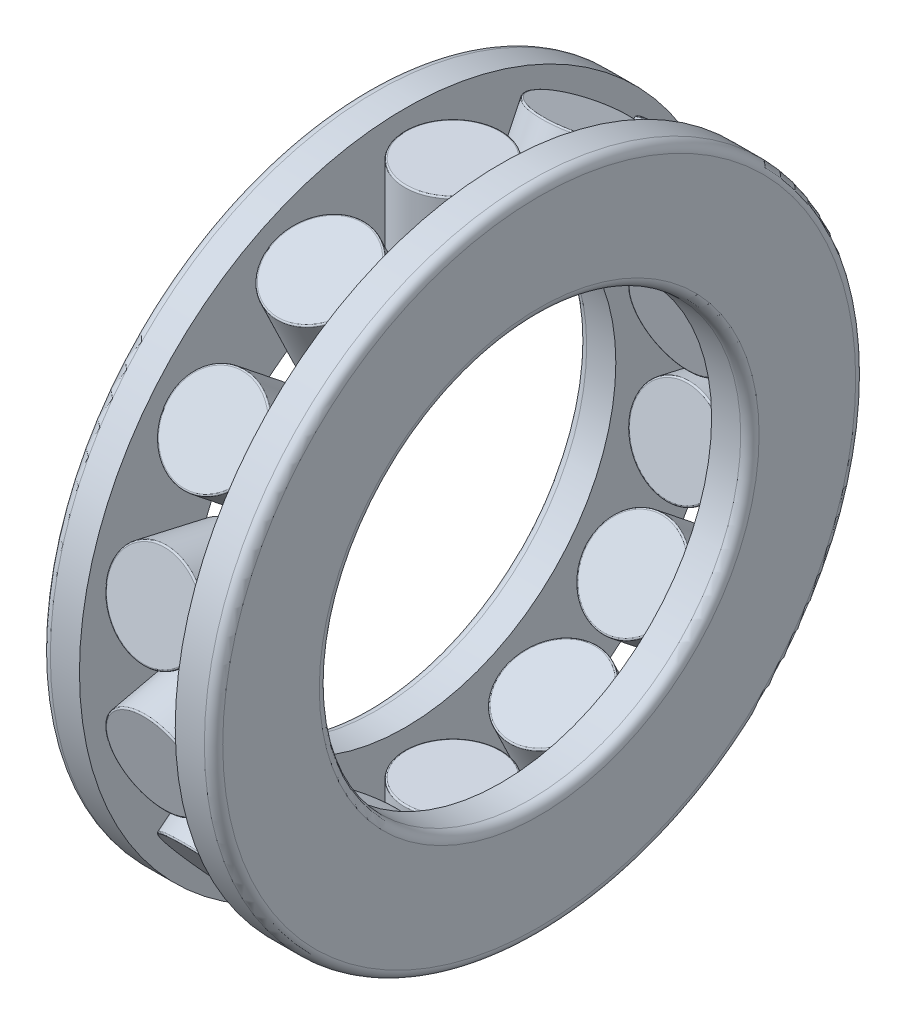
SolidWorks part; units mm, degrees
ref_plane "Plane1" through (0, 0, 0) normal (0, 0, 1) x (1, 0, 0)
ref_plane "Plane2" through (0, 0, 0) normal (0, 1, 0) x (1, 0, 0)
ref_plane "Plane3" through (0, 0, 0) normal (1, 0, 0) x (0, 0, -1)
sketch "Clipboard" plane through (0, 0, 0) normal (0, 0, 1) x (1, 0, 0)
  line L0 (-10, 0) -> (10, 0) construction
  line L1 (0, 0) -> (21.6965, -5.4095)
  line L2 (0, 0) -> (27.3662, 35.0271)
  line L3 (0, 0) -> (13.7666, -17.6205)
  line L4 (0, 0) -> (-22.3471, -0.7804)
  dimension "BallCLRad" = 44.45
  dimension "Count" = 52
  dimension "Show_count" = 52
  dimension "Max_count" = 14
  dimension "Min_count" = 2
sketch "InnRacSke" plane through (0, 0, 0) normal (0, 0, 1) x (1, 0, 0)
  line L1 (-7.9375, 34.925) -> (-12.7635, 34.925)
  line L2 (-14.2875, 36.449) -> (-14.2875, 52.451)
  line L3 (-12.7635, 53.975) -> (-7.9375, 53.975)
  line L4 (-7.9375, 53.975) -> (-7.9375, 34.925)
  line L5 (-34.925, 0) -> (34.925, 0) construction
  line L6 (0, 0) -> (0, 25.4) construction
  arc A0 (-12.7635, 34.925) -> (-14.2875, 36.449) centre (-12.7635, 36.449) cw
  arc A1 (-14.2875, 52.451) -> (-12.7635, 53.975) centre (-12.7635, 52.451) cw
  dimension "ID" = 69.85
  dimension "OD" = 107.95
  dimension "Width" = 28.575
  dimension "gap" = 15.875
revolve "Race" add sketch "InnRacSke" angle 360 about L5
ref_axis "Axis1" through (-50, 0, 0) along (1, 0, 0)
sketch "RolDetSke" plane through (0, 0, 0) normal (0, 0, 1) x (1, 0, 0)
  line L0 (0, 33.02) -> (0, 55.88) construction
  line L3 (0, 50.8) -> (7.7232, 50.8)
  line L4 (0, 50.8) -> (0, 38.1)
  line L5 (0, 38.1) -> (7.7232, 38.1)
  line L6 (7.9772, 50.546) -> (7.9772, 38.354)
  arc A0 (7.9772, 38.354) -> (7.7232, 38.1) centre (7.7232, 38.354) cw
  arc A1 (7.7232, 50.8) -> (7.9772, 50.546) centre (7.7232, 50.546) cw
  dimension "D1" = 0.254
  dimension "Roller_diameter" = 15.9544
  dimension "Cyl_Len" = 12.7
  dimension "offset" = 38.1
revolve "RollerDetailed" add sketch "RolDetSke" angle 360 about L0
sketch "RolSimSke" plane through (0, 0, 0) normal (0, 0, 1) x (1, 0, 0)
  line L1 (-17.78, 0) -> (12.7, 0) construction
  line L3 (-7.7232, 50.8) -> (7.7232, 50.8)
  line L4 (-7.9772, 50.546) -> (-7.9772, 38.354)
  line L5 (-7.7232, 38.1) -> (7.7232, 38.1)
  line L6 (7.9772, 50.546) -> (7.9772, 38.354)
  arc A0 (-7.9772, 38.354) -> (-7.7232, 38.1) centre (-7.7232, 38.354) ccw
  arc A1 (-7.7232, 50.8) -> (-7.9772, 50.546) centre (-7.7232, 50.546) ccw
  arc A2 (7.9772, 50.546) -> (7.7232, 50.8) centre (7.7232, 50.546) ccw
  arc A3 (7.7232, 38.1) -> (7.9772, 38.354) centre (7.7232, 38.354) ccw
  dimension "Roller_diameter" = 15.9544
  dimension "Cyl_Len" = 12.7
  dimension "offset" = 38.1
  dimension "Rol_rad" = 0.254
  dimension "Halfdia" = 7.9772
revolve "RollersSimplified" [suppressed] add sketch "RolSimSke" angle 360 about L1
mirror "Mirror1" about plane through (0, 0, 0) normal (1, 0, 0) of "Race"
pattern_circular "RollersDetailed" count 14 every 25.714 about axis through (-50, 0, 0) along (1, 0, 0) of "RollerDetailed"
sketch "CagSpiSke" plane through (0, 0, 0) normal (0, 0, 1) x (1, 0, 0)
  line L0 (2.3932, 35.6235) -> (2.3932, 52.8955)
  line L1 (2.3932, 52.8955) -> (-2.3932, 52.8955)
  line L2 (-2.3932, 35.6235) -> (-2.3932, 52.8955)
  line L3 (-2.3932, 35.6235) -> (2.3932, 35.6235)
  line L4 (-34.925, 0) -> (34.925, 0) construction
  line L5 (0, 0) -> (0, 63.6264) construction
  dimension "ID" = 71.247
  dimension "OD" = 105.791
  dimension "Thickness" = 4.7863
revolve "CageSpine" [suppressed] add sketch "CagSpiSke" angle 360 about L4
equation "\"BallCLRad@Clipboard\" =  ( \"OD@InnRacSke\" + \"ID@InnRacSke\" )  / 4"
equation "\"offset@RolDetSke\" = \"BallCLRad@Clipboard\" - \"Cyl_Len@RolDetSke\" / 2"
equation "\"Cyl_Len@RolSimSke\" = \"Cyl_Len@RolDetSke\""
equation "\"offset@RolSimSke\" = \"BallCLRad@Clipboard\" - \"Cyl_Len@RolSimSke\" / 2"
equation "\"Roller_diameter@RolDetSke\" = \"gap@InnRacSke\" * 1.005"
equation "\"Roller_diameter@RolSimSke\" = \"gap@InnRacSke\" * 1.005"
equation "\"Max_count@Clipboard\" = int( 3.14159265 / atn(( \"Roller_diameter@RolDetSke\" / 2) / sqr( \"offset@RolDetSke\"  *  \"offset@RolDetSke\" - ( \"Roller_diameter@RolDetSke\" / 2) *  ( \"Roller_diameter@RolDetSke\" / 2))))"
equation "\"Max_count@Clipboard\" = ((sgn( \"Max_count@Clipboard\" - \"Count@Clipboard\" )-1)*( \"Max_count@Clipboard\" - \"Count@Clipboard\" ))/-2+ \"Count@Clipboard\""
equation "\"Count@RollersDetailed\" = int( \"Show_count@Clipboard\" ) "
equation "\"Count@RollersDetailed\" = ((sgn( \"Count@RollersDetailed\" - \"Max_count@Clipboard\" )-1)*( \"Count@RollersDetailed\" - \"Max_count@Clipboard\" ))/-2+ \"Max_count@Clipboard\""
equation "\"Count@RollersDetailed\" = ((sgn( \"Count@RollersDetailed\" - \"Min_count@Clipboard\" )+1)*( \"Count@RollersDetailed\" - \"Min_count@Clipboard\"))/2 +\"Min_count@Clipboard\""
equation "\"Angle@RollersDetailed\" = 360.0 / \"Max_count@Clipboard\""
equation "\"Angle@CageSpine\" =  \"Angle@RollersDetailed\" * ( \"Count@RollersDetailed\" -1 + int( \"Count@RollersDetailed\" / \"Max_count@Clipboard\" ) )  + 0.001 -  int( \"Count@RollersDetailed\" / \"Max_count@Clipboard\" ) * 0.001"
equation "\"Angle@CageSpine\" =  \"Angle@CageSpine\" * int( \"Min_count@Clipboard\" / 2) + int(1 / \"Min_count@Clipboard\")  * 0.001"
equation "\"Thickness@CagSpiSke\" =  \"Roller_diameter@RolDetSke\" * 0.3"
equation "\"OD@CagSpiSke\" =  \"OD@InnRacSke\" * 0.98"
equation "\"ID@CagSpiSke\" =  \"ID@InnRacSke\" * 1.02"
equation "\"Halfdia@RolSimSke\" = \"Roller_diameter@RolSimSke\" / 2"
